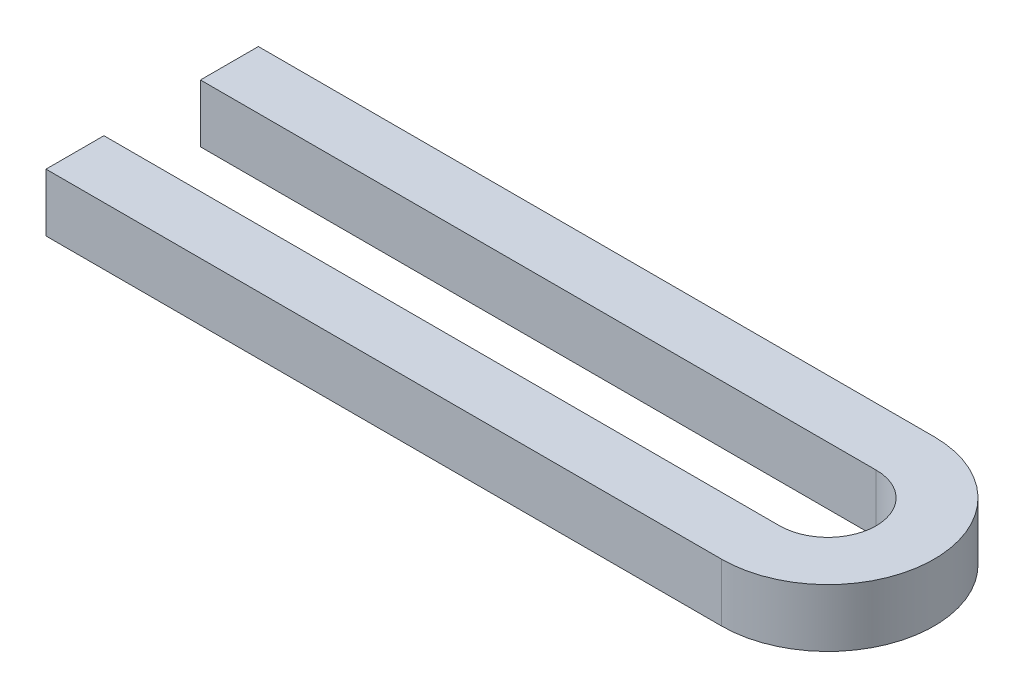
SolidWorks part; units mm, degrees
ref_plane "前视基准面" through (0, 0, 0) normal (0, 0, 1) x (1, 0, 0)
ref_plane "上视基准面" through (0, 0, 0) normal (0, 1, 0) x (1, 0, 0)
ref_plane "右视基准面" through (0, 0, 0) normal (1, 0, 0) x (0, 0, -1)
other "Configuration Table"
sketch "草图1" plane through (0, 0, 0) normal (0, 1, 0) x (1, 0, 0)
  line L0 (0, 0) -> (-10.1449, 0) construction
  line L1 (0, 2.5) -> (-35, 2.5)
  line L2 (0, -2.5) -> (-35, -2.5)
  line L3 (0, -5.5) -> (-35, -5.5)
  line L4 (0, 5.5) -> (-35, 5.5)
  line L5 (-35, 5.5) -> (-35, 2.5)
  line L6 (-35, -2.5) -> (-35, -5.5)
  arc A0 (0, 2.5) -> (0, -2.5) centre (0, 0) cw
  arc A1 (0, 5.5) -> (0, -5.5) centre (0, 0) cw
  dimension "D1" = 2.5
  dimension "D2" = 35
  dimension "D3" = 2.5
  dimension "D4" = 3
extrude "凸台-拉伸1" add sketch "草图1" along normal blind 3
